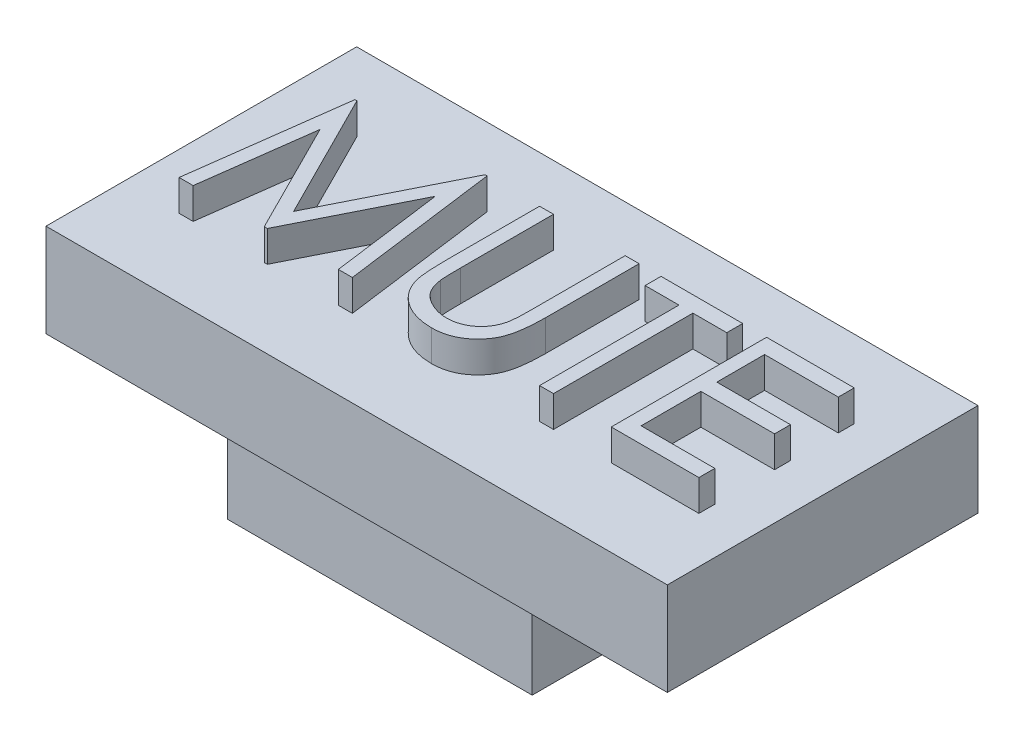
SolidWorks part; units mm, degrees
ref_plane "Front Plane" through (0, 0, 0) normal (0, 0, 1) x (1, 0, 0)
ref_plane "Top Plane" through (0, 0, 0) normal (0, 1, 0) x (1, 0, 0)
ref_plane "Right Plane" through (0, 0, 0) normal (1, 0, 0) x (0, 0, -1)
sketch "Sketch1" plane through (0, 0, 0) normal (0, 1, 0) x (1, 0, 0)
  line L1 (-10, -5) -> (10, -5)
  line L2 (-10, -5) -> (-10, 5)
  line L3 (-10, 5) -> (10, 5)
  line L4 (10, -5) -> (10, 5)
  line L5 (-10, -5) -> (10, 5) construction
  line L6 (-10, 5) -> (10, -5) construction
  point P0 (0, 0)
  dimension "D1" = 20
  dimension "D2" = 10
extrude "Boss-Extrude1" add sketch "Sketch1" along normal blind 3
sketch "Sketch2" plane through (0, 0, 0) normal (0, -1, 0) x (1, 0, 0)
  line L1 (-2.9, -2.25) -> (2.9, -2.25)
  line L2 (-2.9, -2.25) -> (-2.9, 2.25)
  line L3 (-2.9, 2.25) -> (2.9, 2.25)
  line L4 (2.9, -2.25) -> (2.9, 2.25)
  line L5 (-2.9, -2.25) -> (2.9, 2.25) construction
  line L6 (-2.9, 2.25) -> (2.9, -2.25) construction
  line L7 (-4.9, -4.25) -> (4.9, -4.25)
  line L8 (-4.9, -4.25) -> (-4.9, 4.25)
  line L9 (-4.9, 4.25) -> (4.9, 4.25)
  line L10 (4.9, -4.25) -> (4.9, 4.25)
  line L11 (-4.9, -4.25) -> (4.9, 4.25) construction
  line L12 (-4.9, 4.25) -> (4.9, -4.25) construction
  point P0 (0, 0)
  point P6 (0, 0)
  dimension "D1" = 4.5
  dimension "D2" = 5.8
  dimension "D3" = 2
  dimension "D4" = 2
extrude "Boss-Extrude2" add sketch "Sketch2" along normal blind 3
sketch "Sketch3" plane through (0, 3, 0) normal (0, 1, 0) x (1, 0, 0)
  text T0 "MUTE" font "Century Gothic" height 5
  dimension "D1" = 2.5
  dimension "D2" = 8.6
extrude "Boss-Extrude3" add sketch "Sketch3" along normal blind 1
